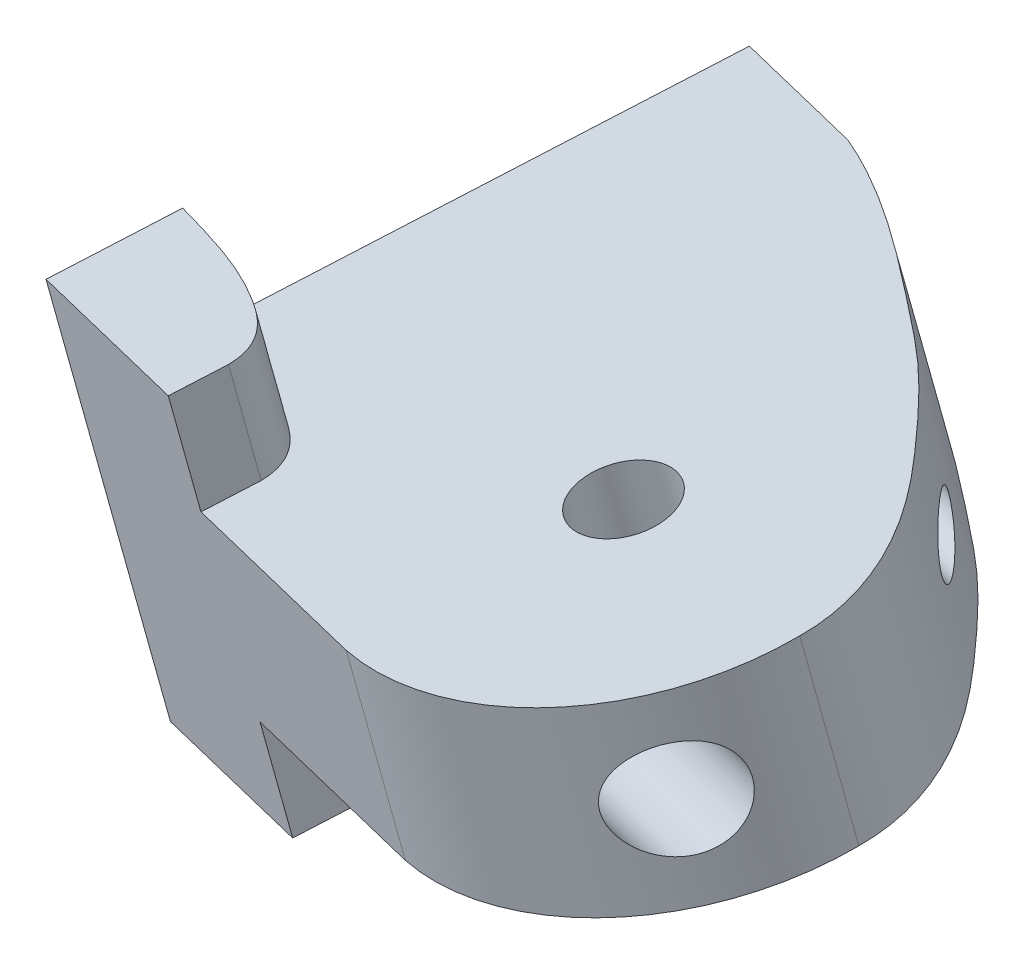
SolidWorks part; units mm, degrees
ref_plane "Front Plane" through (0, 0, 0) normal (0, 0, 1) x (1, 0, 0)
ref_plane "Top Plane" through (0, 0, 0) normal (0, 1, 0) x (1, 0, 0)
ref_plane "Right Plane" through (0, 0, 0) normal (1, 0, 0) x (0, 0, -1)
sketch "Sketch6" plane through (10.6326, -81.0954, -14.9974) normal (-0.1279, 0.9753, 0.1804) x (0.9918, 0.1257, 0.0233)
  line L1 (-66.8718, -76.3056) -> (-74.0508, -74.2873) construction
  line L2 (-60.9177, -55.1266) -> (-51.9291, -57.6536) construction
  line L3 (-60.9177, -55.1266) -> (-68.0967, -53.1083) construction
  line L5 (-58.7207, -78.5971) -> (-74.0508, -74.2873)
  line L6 (-74.0508, -74.2873) -> (-68.0967, -53.1083)
  line L7 (-68.0967, -53.1083) -> (-62.4521, -54.6952)
  circle A0 centre (-56.4755, -69.6309) radius 1.75
  arc A1 (-58.7207, -78.5971) -> (-47.4128, -71.4482) centre (-56.4755, -69.6309) ccw
  spline S1 degree 3 poles (-47.4128, -71.4482) (-46.9884, -69.5424) (-48.131, -66.4955) (-50.8996, -63.2697) (-53.0306, -61.0254) (-55.4212, -59.1852) (-58.2857, -56.9853) (-60.7445, -55.4337) (-62.4521, -54.6952) knots 0 0 0 0 0.242005 0.382339 0.541587 0.632723 0.764707 1 1 1 1
extrude "Boss-Extrude2" add sketch "Sketch6" along normal up to surface (8 mm away)
sketch "Sketch7" plane through (-24.5757, -19.1439, 86.0935) normal (-0.2684, -0.2091, 0.9403) x (0.9633, -0.0583, 0.262)
  line L0 (-40.7532, -81.2818) -> (-39.6913, -89.2111) construction
  line L1 (-40.7532, -81.2818) -> (-24.9697, -79.1681) construction
  line L2 (-40.7532, -81.2818) -> (-39.6913, -89.2111) construction
  line L3 (-40.2222, -85.2465) -> (-48.1754, -86.3116) construction
  line L4 (-40.7266, -81.4801) -> (-46.2314, -82.2173)
  line L5 (-46.2314, -82.2173) -> (-46.6647, -78.9818)
  line L6 (-46.6647, -78.9818) -> (-9.7098, -74.0327)
  line L7 (-9.7098, -74.0327) -> (-9.2765, -77.2682)
  line L8 (-9.2765, -77.2682) -> (-40.7266, -81.4801)
  line L9 (-8.2677, -84.8009) -> (-39.7178, -89.0128)
  line L10 (-7.8344, -88.0364) -> (-8.2677, -84.8009)
  line L11 (-44.7893, -92.9855) -> (-7.8344, -88.0364)
  line L12 (-45.2226, -89.75) -> (-44.7893, -92.9855)
  line L13 (-39.7178, -89.0128) -> (-45.2226, -89.75)
  dimension "D1" = 7.6
extrude "Cut-Extrude4" cut sketch "Sketch7" against normal through all both and the other way through all
sketch "Sketch8" plane through (-48.8672, -3.6762, -14.7668) normal (-0.9548, -0.0718, -0.2885) x (-0.2877, -0.0216, 0.9575)
  line L0 (75.0073, -94.9824) -> (53.4011, -90.8383) construction
  line L1 (75.7231, -91.2505) -> (74.2915, -98.7144) construction
  line L2 (54.1169, -87.1063) -> (52.6853, -94.5703) construction
  circle A0 centre (58.3116, -91.7802) radius 1
  circle A1 centre (69.6057, -93.9464) radius 2
  dimension "D2" = 2
  dimension "D3" = 4
  dimension "D1" = 5
  dimension "D4" = 5.5
extrude "Cut-Extrude5" cut sketch "Sketch8" against normal through all both and the other way through all
sketch "Sketch9" plane through (9.6352, -73.4884, -13.5906) normal (-0.1279, 0.9753, 0.1804) x (0.9918, 0.1257, 0.0233)
  line L0 (-72.8374, -69.9712) -> (-74.0508, -74.2873)
  line L1 (-58.7207, -78.5971) -> (-74.0508, -74.2873) construction
  line L2 (-74.0508, -74.2873) -> (-68.0967, -53.1083) construction
  line L4 (-66.5096, -74.3571) -> (-67.0438, -76.2572)
  line L5 (-74.0508, -74.2873) -> (-67.0438, -76.2572)
  spline S0 degree 3 poles (-66.5096, -74.3571) (-66.2813, -73.1495) (-68.6197, -71.2537) (-71.1849, -70.4872) (-72.8374, -69.9712) knots 0 0 0 0 0.375546 1 1 1 1
extrude "Boss-Extrude3" add sketch "Sketch9" along normal up to surface (4.2 mm away)
sketch "Sketch10" plane through (10.607, -80.9003, -14.9613) normal (0.1279, -0.9753, -0.1804) x (0.9918, 0.1257, 0.0233)
  line L0 (-67.0438, 76.2572) -> (-66.5096, 74.3571)
  line L1 (-74.0508, 74.2873) -> (-58.7207, 78.5971) construction
  line L2 (-67.0438, 76.2572) -> (-66.5096, 74.3571) construction
  line L3 (-74.0508, 74.2873) -> (-72.8374, 69.9712)
  line L4 (-68.0967, 53.1083) -> (-74.0508, 74.2873) construction
  line L5 (-74.0508, 74.2873) -> (-67.0438, 76.2572)
  spline S0 degree 3 poles (-66.5096, 74.3571) (-66.3704, 73.7937) (-66.7803, 72.7053) (-68.4022, 71.6359) (-70.3875, 70.7173) (-72.0299, 70.225) (-72.8374, 69.9712) knots 0 0 0 0 0.205425 0.379783 0.692407 1 1 1 1
  spline S1 degree 3 poles (-66.5096, 74.3571) (-66.2813, 73.1495) (-68.6197, 71.2537) (-71.1849, 70.4872) (-72.8374, 69.9712) knots 0 0 0 0 0.375546 1 1 1 1 construction
extrude "Boss-Extrude4" add sketch "Sketch10" along normal up to surface (4.2 mm away)
